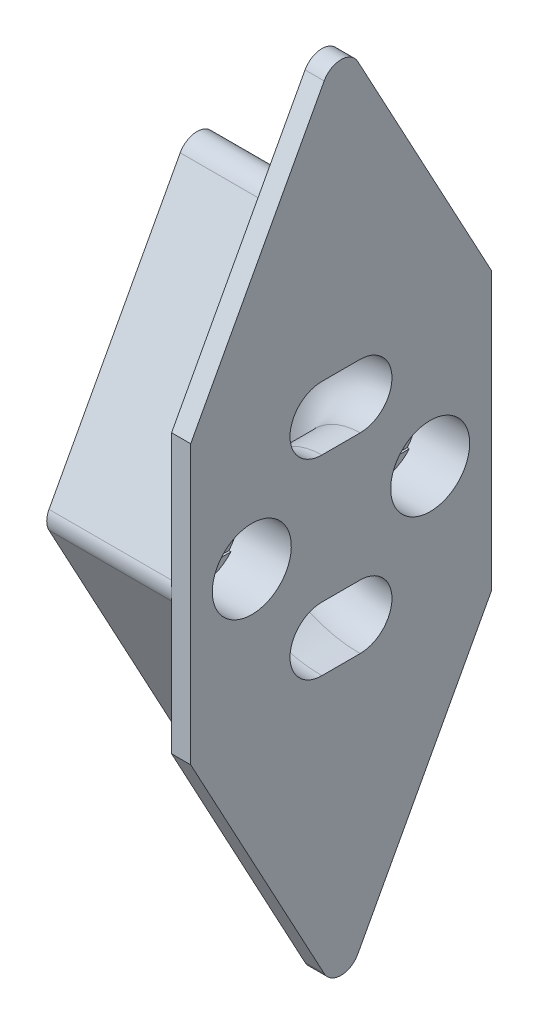
SolidWorks part; units mm, degrees
ref_plane "Front" through (0, 0, 0) normal (0, 0, 1) x (1, 0, 0)
ref_plane "Top" through (0, 0, 0) normal (0, 1, 0) x (1, 0, 0)
ref_plane "Right" through (0, 0, 0) normal (1, 0, 0) x (0, 0, -1)
sketch "Sketch1" plane through (0, 0, 0) normal (1, 0, 0) x (0, 0, -1)
  line L1 (0, -28.2575) -> (15.24, 0)
  line L2 (0, -28.2575) -> (-15.24, 0)
  line L3 (-15.24, 0) -> (0, 28.2575)
  line L4 (15.24, 0) -> (0, 28.2575)
  line L5 (0, -28.2575) -> (0, 28.2575) construction
  line L6 (-15.24, 0) -> (15.24, 0) construction
  point P0 (0, 0)
  dimension "D1" = 30.48
  dimension "D2" = 56.515
extrude "Boss-Extrude1" add sketch "Sketch1" along normal blind 12.446
sketch "Sketch6" plane through (12.446, 0, 0) normal (1, 0, 0) x (0, 0, -1)
  line L14 (-22.4547, 0) -> (0, -41.6347)
  line L15 (0, -41.6347) -> (22.4547, 0)
  line L16 (22.4547, 0) -> (0, 41.6347)
  line L17 (0, 41.6347) -> (-22.4547, 0)
  line L18 (-22.4547, 0) -> (0, -41.6347)
  line L19 (0, -41.6347) -> (22.4547, 0)
  line L20 (22.4547, 0) -> (0, 41.6347)
  line L21 (0, 41.6347) -> (-22.4547, 0)
  dimension "D1" = 6.35
extrude "Boss-Extrude3" add sketch "Sketch6" along normal blind 1.905
fillet "Fillet1" radius 1.905 8 edges at (13.3985, 41.6347, 0) (13.3985, 0, 22.4547) (13.3985, -41.6347, 0) (13.3985, 0, -22.4547) (6.223, -28.2575, 0) (6.223, 0, -15.24) (6.223, 0, 15.24) (6.223, 28.2575, 0)
sketch "Sketch7" plane through (0, 0, 0) normal (0, 1, 0) x (1, 0, 0)
  line L0 (0, 0) -> (25.2725, 0) construction
  line L1 (14.351, 0) -> (14.351, -10.3712) construction
  line L3 (4.826, -1.905) -> (4.826, 1.905) construction
  line L4 (1.651, -1.905) -> (1.651, 1.905)
  line L5 (8.001, -1.905) -> (8.001, 1.905)
  line L6 (14.351, -1.6767) -> (14.351, 1.6767) construction
  arc A1 (1.651, -1.905) -> (8.001, -1.905) centre (4.826, -1.905) ccw
  arc A2 (8.001, 1.905) -> (1.651, 1.905) centre (4.826, 1.905) ccw
  point P7 (4.826, 0)
  point P14 (12.446, 0)
  point P15 (14.351, 0)
  dimension "D1" = 6.35
  dimension "D2" = 10.16
  dimension "D3" = 6.35
revolve "Cut-Revolve2" cut sketch "Sketch7" angle 360 about L1
sketch "Sketch8" plane through (14.351, 0, 0) normal (1, 0, 0) x (0, 0, -1)
  line L0 (0, 0) -> (8.89, 0) construction
  line L1 (0, 0) -> (0, 3.2594) construction
  circle A0 centre (8.89, 0) radius 3.937
  circle A1 centre (-8.89, 0) radius 3.937
  dimension "D2" = 7.874
  dimension "D1" = 8.89
extrude "Cut-Extrude3" cut sketch "Sketch8" against normal blind 5.08
sketch "Sketch9" plane through (9.271, 0, 0) normal (1, 0, 0) x (0, 0, -1)
  line L0 (0, 0) -> (0, 4.0921) construction
  circle A0 centre (8.89, 0) radius 2.5527
  circle A1 centre (-8.89, 0) radius 2.5527
  dimension "D1" = 5.1054
extrude "Cut-Extrude4" cut sketch "Sketch9" against normal through all
sketch "Sketch10" [suppressed] plane through (15.875, 0, 0) normal (1, 0, 0) x (0, 0, -1)
  line L0 (0, 0) -> (0, 8.2156) construction
  line L1 (13.6525, 2.7496) -> (8.89, 5.4993)
  line L2 (8.89, 5.4993) -> (4.1275, 2.7496)
  line L3 (4.1275, 2.7496) -> (4.1275, -2.7496)
  line L4 (4.1275, -2.7496) -> (8.89, -5.4993)
  line L5 (8.89, -5.4993) -> (13.6525, -2.7496)
  line L6 (13.6525, -2.7496) -> (13.6525, 2.7496)
  line L7 (-13.6525, -2.7496) -> (-13.6525, 2.7496)
  line L8 (-8.89, -5.4993) -> (-13.6525, -2.7496)
  line L9 (-4.1275, -2.7496) -> (-8.89, -5.4993)
  line L10 (-4.1275, 2.7496) -> (-4.1275, -2.7496)
  line L11 (-8.89, 5.4993) -> (-4.1275, 2.7496)
  line L12 (-13.6525, 2.7496) -> (-8.89, 5.4993)
  circle A0 centre (8.89, 0) radius 4.7625 construction
  circle A1 centre (-8.89, 0) radius 4.7625 construction
  point P1 (13.6525, 0)
  dimension "D1" = 9.525
sketch "Sketch11" [suppressed] plane through (15.621, 0, 0) normal (1, 0, 0) x (0, 0, -1)
  line L0 (0, 0) -> (8.89, 0) construction
  line L1 (0, 0) -> (0, 10.0261) construction
  circle A0 centre (8.89, 0) radius 3.175
  circle A1 centre (-8.89, 0) radius 3.175
  dimension "D2" = 6.35
  dimension "D1" = 8.89
extrude "Cut-Extrude6" [suppressed] cut sketch "Sketch11" against normal through all
sketch "Sketch12" plane through (12.446, 0, 0) normal (-1, 0, 0) x (0, 0, 1)
  line L0 (-14.9806, -13.8581) -> (-14.9806, 13.8581)
  line L1 (-1.6767, -38.5258) -> (-21.9669, -0.9043) construction
  line L2 (-21.9669, 0.9043) -> (-1.6767, 38.5258) construction
  line L4 (14.9806, -13.8581) -> (14.9806, 13.8581)
  line L5 (21.9669, -0.9043) -> (1.6767, -38.5258) construction
  line L6 (1.6767, 38.5258) -> (21.9669, 0.9043) construction
  line L7 (-14.9806, -13.8581) -> (-21.9669, -0.9043)
  line L8 (21.9669, -0.9043) -> (14.9806, -13.8581)
  line L9 (14.9806, 13.8581) -> (21.9669, 0.9043)
  line L10 (-21.9669, 0.9043) -> (-14.9806, 13.8581)
  arc A0 (-14.7523, 0.9043) -> (-14.7523, -0.9043) centre (-13.0756, 0) ccw construction
  arc A3 (21.9669, -0.9043) -> (21.9669, 0.9043) centre (20.2903, 0) ccw construction
  arc A4 (-21.9669, 0.9043) -> (-21.9669, -0.9043) centre (-20.2903, 0) ccw construction
  arc A5 (21.9669, -0.9043) -> (21.9669, 0.9043) centre (20.2903, 0) ccw
  arc A6 (-21.9669, 0.9043) -> (-21.9669, -0.9043) centre (-20.2903, 0) ccw
  arc A8 (14.7523, -0.9043) -> (14.7523, 0.9043) centre (13.0756, 0) ccw construction
  point P7 (-14.9806, 0)
  point P11 (14.9806, 0)
extrude "Cut-Extrude7" cut sketch "Sketch12" against normal through all
sketch "Sketch13" plane through (9.271, 0, 0) normal (1, 0, 0) x (0, 0, -1)
  line L1 (5.8927, 2.5527) -> (11.8873, 2.5527)
  line L3 (5.8927, -2.5527) -> (11.8873, -2.5527)
  line L5 (-11.8873, 2.5527) -> (-5.8927, 2.5527)
  line L7 (-11.8873, -2.5527) -> (-5.8927, -2.5527)
  circle A0 centre (8.89, 0) radius 3.937 construction
  circle A1 centre (8.89, 0) radius 3.937 construction
  circle A2 centre (-8.89, 0) radius 3.937 construction
  circle A3 centre (-8.89, 0) radius 2.5527 construction
  circle A4 centre (8.89, 0) radius 2.5527 construction
  circle A5 centre (-8.89, 0) radius 3.937 construction
  arc A6 (5.8927, 2.5527) -> (5.8927, -2.5527) centre (8.89, 0) ccw
  arc A7 (-11.8873, 2.5527) -> (-11.8873, -2.5527) centre (-8.89, 0) ccw
  arc A8 (-5.8927, -2.5527) -> (-5.8927, 2.5527) centre (-8.89, 0) ccw
  arc A9 (11.8873, -2.5527) -> (11.8873, 2.5527) centre (8.89, 0) ccw
  point P16 (0, 0)
extrude "Cut-Extrude8" cut sketch "Sketch13" against normal blind 0.2
sketch "Sketch14" plane through (9.071, 0, 0) normal (1, 0, 0) x (0, 0, -1)
  line L0 (11.8873, 2.5527) -> (5.8927, 2.5527) construction
  line L1 (6.3373, 2.5527) -> (11.4427, 2.5527)
  line L2 (6.3373, 2.5527) -> (6.3373, -2.5527)
  line L3 (6.3373, -2.5527) -> (11.4427, -2.5527)
  line L4 (11.4427, 2.5527) -> (11.4427, -2.5527)
  line L5 (8.89, -2.5527) -> (11.8873, -2.5527) construction
  line L6 (-5.8927, 2.5527) -> (-11.8873, 2.5527) construction
  line L7 (-11.4427, 2.5527) -> (-6.3373, 2.5527)
  line L8 (-11.4427, 2.5527) -> (-11.4427, -2.5527)
  line L9 (-11.4427, -2.5527) -> (-6.3373, -2.5527)
  line L10 (-6.3373, 2.5527) -> (-6.3373, -2.5527)
  line L11 (-11.8873, -2.5527) -> (-5.8927, -2.5527) construction
  arc A0 (-8.89, 2.5527) -> (-8.89, -2.5527) centre (-8.89, 0) ccw construction
  arc A1 (-8.89, -2.5527) -> (-8.89, 2.5527) centre (-8.89, 0) ccw construction
  arc A2 (8.89, 2.5527) -> (8.89, -2.5527) centre (8.89, 0) ccw construction
  arc A3 (8.89, -2.5527) -> (8.89, 2.5527) centre (8.89, 0) ccw construction
extrude "Cut-Extrude9" cut sketch "Sketch14" against normal blind 0.2
